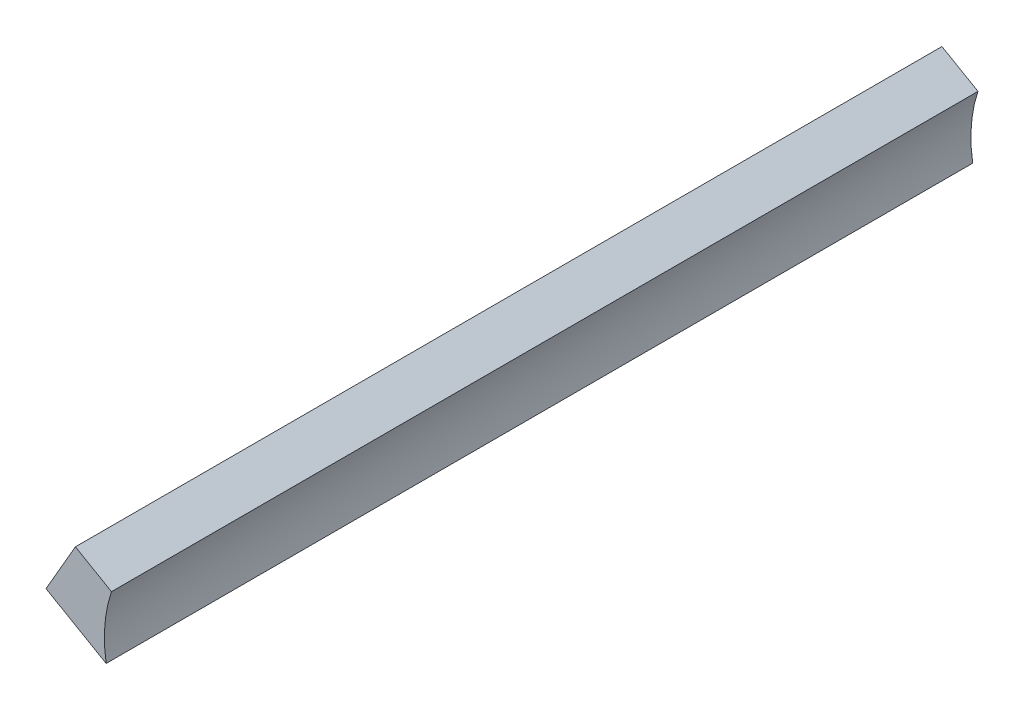
SolidWorks part; units mm, degrees
ref_plane "Front Plane" through (0, 0, 0) normal (0, 0, 1) x (1, 0, 0)
ref_plane "Top Plane" through (0, 0, 0) normal (0, 1, 0) x (1, 0, 0)
ref_plane "Right Plane" through (0, 0, 0) normal (1, 0, 0) x (0, 0, -1)
sketch "Sketch1" plane through (0, 0, 1031.1039) normal (0, 0, 1) x (1, 0, 0)
  line L0 (287.2837, 598.672) -> (310.6423, 585.1863)
  line L1 (268.2337, 565.6764) -> (307.2038, 543.1777)
  line L2 (200469.115, 557.3071) -> (-199683.285, 557.3071) construction
  line L3 (287.2837, 598.672) -> (268.2337, 565.6764)
  arc A0 (315.6307, 596.9705) -> (306.4192, 565.3399) centre (392.915, 557.3071) ccw construction
  arc A1 (310.6423, 585.1863) -> (307.2038, 543.1777) centre (392.915, 557.3071) ccw
extrude "Boss-Extrude1" add sketch "Sketch1" along normal up to surface (25.4 mm away) and the other way up to surface (535.94 mm away)
sketch "Sketch2" plane through (-43.7698, 25.2705, 0) normal (-0.866, 0.5, 0) x (0, 0, 1)
  circle A0 centre (775.6712, 643.2157) radius 6.35
  circle A1 centre (929.5952, 643.2157) radius 6.35
  circle A2 centre (621.7472, 643.2157) radius 6.35
  dimension "D3" = 153.924
  dimension "D4" = 153.924
  dimension "D1" = 2
  dimension "D2" = 2
extrude "Cut-Extrude1" cut sketch "Sketch2" against normal blind 19
ref_plane "Plane1" through (0, 0, 1056.5039) normal (0, 0, 1) x (0.866, -0.5, 0)
equation "\"PRESS_TOP_FACE_WIDTH\"=1.06189"
equation "\"SCREW_HOLE_SPACING\"=6.06"
equation "\"D3@Sketch2\"=\"SCREW_HOLE_SPACING\""
equation "\"D4@Sketch2\"=\"SCREW_HOLE_SPACING\""
